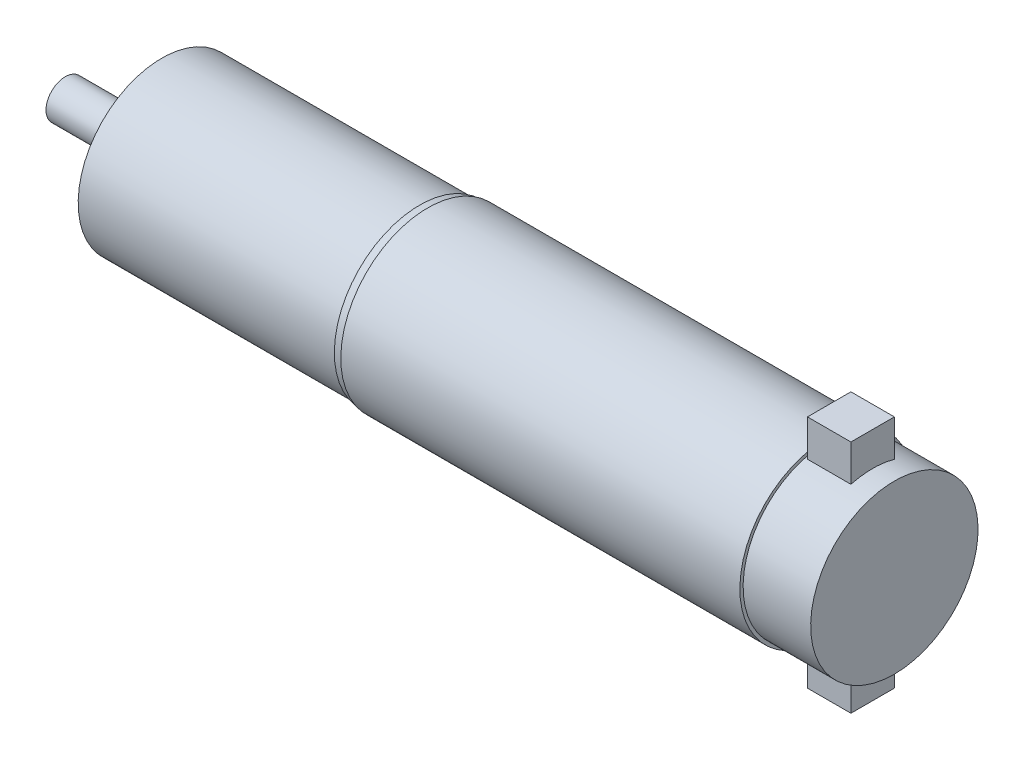
SolidWorks part; units mm, degrees
ref_plane "Front Plane" through (0, 0, 0) normal (0, 0, 1) x (1, 0, 0)
ref_plane "Top Plane" through (0, 0, 0) normal (0, 1, 0) x (1, 0, 0)
ref_plane "Right Plane" through (0, 0, 0) normal (1, 0, 0) x (0, 0, -1)
sketch "Sketch1" plane through (0, 0, 0) normal (0, 0, 1) x (1, 0, 0)
  line L0 (-30, 26) -> (227.6, 26) construction
  line L1 (0, 0) -> (80.1, 0)
  line L2 (0, 0) -> (0, 52)
  line L3 (0, 52) -> (80.1, 52)
  line L4 (80.1, 0) -> (80.1, 52)
  line L5 (80.1, -0.5) -> (82.6, -0.5)
  line L6 (80.1, -0.5) -> (80.1, 52.5)
  line L7 (80.1, 52.5) -> (82.6, 52.5)
  line L8 (82.6, -0.5) -> (82.6, 52.5)
  line L9 (82.6, -1) -> (206.6, -1)
  line L10 (82.6, -1) -> (82.6, 53)
  line L11 (82.6, 53) -> (206.6, 53)
  line L12 (206.6, -1) -> (206.6, 53)
  line L13 (206.6, 52) -> (227.6, 52)
  line L14 (206.6, 52) -> (206.6, 0)
  line L15 (206.6, 0) -> (227.6, 0)
  line L16 (227.6, 52) -> (227.6, 0)
  line L17 (0, 42) -> (-2, 42)
  line L18 (0, 42) -> (0, 10)
  line L19 (0, 10) -> (-2, 10)
  line L20 (-2, 42) -> (-2, 10)
  line L21 (-2, 32) -> (-30, 32)
  line L22 (-2, 32) -> (-2, 20)
  line L23 (-2, 20) -> (-30, 20)
  line L24 (-30, 32) -> (-30, 20)
  point P17 (81.35, -0.5)
  point P18 (82.6, 26)
  point P19 (80.1, 26)
  point P20 (82.6, 26)
  point P21 (206.6, 26)
  point P30 (0, 26)
  point P31 (-30, 26)
  point P33 (-2, 26)
  dimension "D1" = 80.1
  dimension "D2" = 52
  dimension "D3" = 124
  dimension "D4" = 54
  dimension "D5" = 52
  dimension "D6" = 21
  dimension "D7" = 53
  dimension "D8" = 2.5
  dimension "D9" = 2
  dimension "D10" = 32
  dimension "D11" = 12
  dimension "D12" = 28
revolve "Revolve1" add sketch "Sketch1" angle 360 about L0
sketch "Sketch2" plane through (0, 0, 0) normal (0, 1, 0) x (1, 0, 0)
  line L0 (227.6, -26) -> (227.6, 26) construction
  line L1 (207.35, 6.75) -> (220.85, 6.75)
  line L2 (207.35, 6.75) -> (207.35, -6.75)
  line L3 (207.35, -6.75) -> (220.85, -6.75)
  line L4 (220.85, 6.75) -> (220.85, -6.75)
  line L5 (227.6, 0) -> (206.6, 0) construction
  point P4 (214.1, 6.75)
  point P8 (220.85, 0)
  dimension "D1" = 13.5
  dimension "D2" = 13.5
  dimension "D3" = 13.5
extrude "Boss-Extrude1" add sketch "Sketch2" along normal mid plane 73 from offset 26
